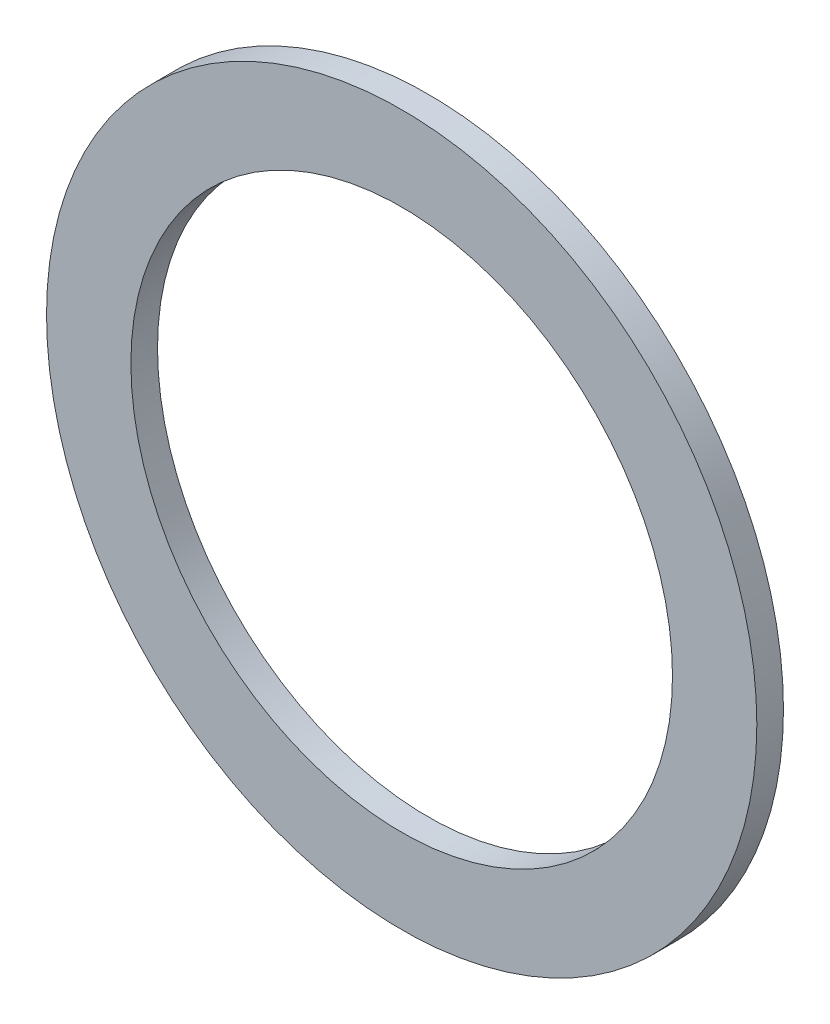
SolidWorks part; units mm, degrees
material "PTFE (general)"
ref_plane "Front Plane" through (0, 0, 0) normal (0, 0, 1) x (1, 0, 0)
ref_plane "Top Plane" through (0, 0, 0) normal (0, 1, 0) x (1, 0, 0)
ref_plane "Right Plane" through (0, 0, 0) normal (1, 0, 0) x (0, 0, -1)
sketch "Sketch1" plane through (0, 0, 0) normal (0, 0, 1) x (1, 0, 0)
  circle A0 centre (0, 0) radius 2
  circle A1 centre (0, 0) radius 1.525
extrude "PTFE_Thrust_Film_H0p15" add sketch "Sketch1" along normal blind 0.15 from offset 1.8
